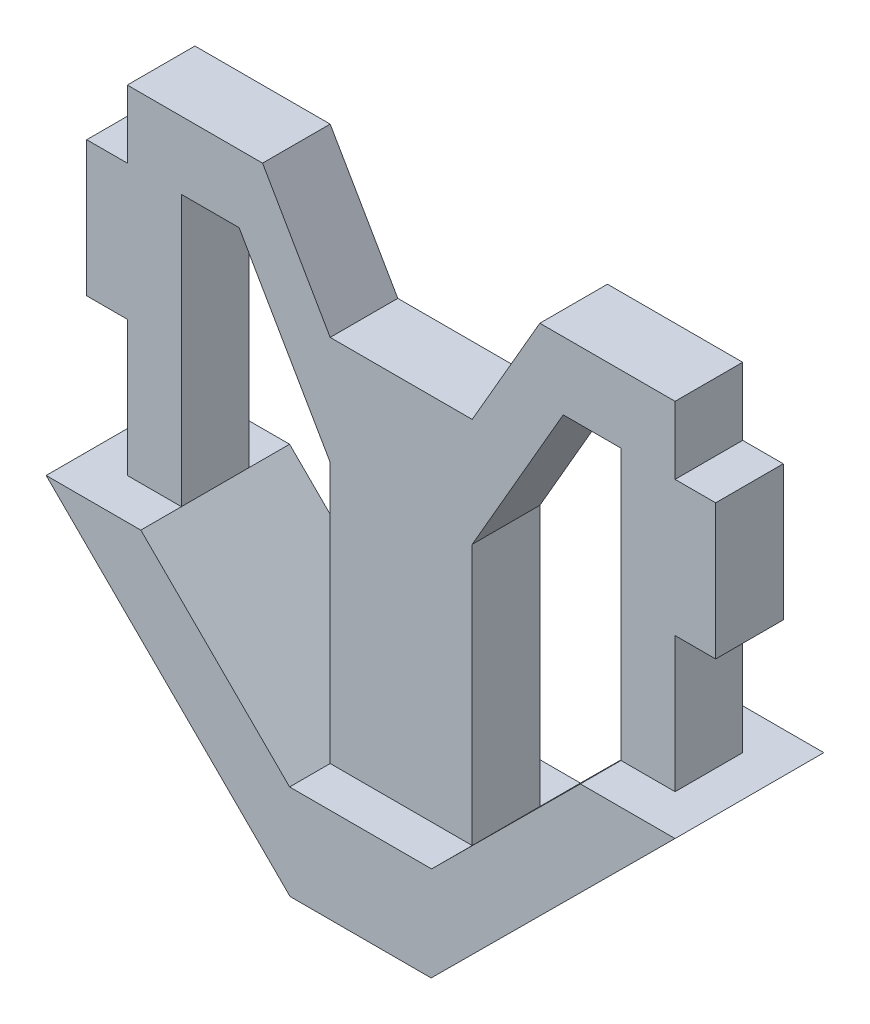
SolidWorks part; units mm, degrees
ref_plane "Front" through (0, 0, 0) normal (0, 0, 1) x (1, 0, 0)
ref_plane "Top" through (0, 0, 0) normal (0, 1, 0) x (1, 0, 0)
ref_plane "Right" through (0, 0, 0) normal (1, 0, 0) x (0, 0, -1)
sketch "草图1" plane through (0, 0, 0) normal (0, 0, 1) x (1, 0, 0)
  line L0 (0, 31.8102) -> (0, 0) construction
  line L1 (-5.2514, 27.286) -> (5.2514, 27.286)
  line L2 (5.2514, 27.286) -> (10.2514, 35.9462)
  line L3 (10.2514, 35.9462) -> (20.2514, 35.9462)
  line L4 (-5.2514, 27.286) -> (-10.2514, 35.9462)
  line L5 (-5.2514, 19.286) -> (-11.9835, 30.9462)
  line L6 (20.2514, 35.9462) -> (20.2514, 30.9462)
  line L7 (20.2514, 30.9462) -> (23.2514, 30.9462)
  line L8 (23.2514, 30.9462) -> (23.2514, 20.9462)
  line L9 (23.2514, 20.9462) -> (20.2514, 20.9462)
  line L10 (20.2514, 20.9462) -> (20.2514, 10.9462)
  line L11 (20.2514, 10.9462) -> (16.2514, 10.9462)
  line L12 (-20.2514, 35.9462) -> (-20.2514, 30.9462)
  line L13 (-20.2514, 30.9462) -> (-23.2514, 30.9462)
  line L14 (-23.2514, 30.9462) -> (-23.2514, 20.9462)
  line L15 (-23.2514, 20.9462) -> (-20.2514, 20.9462)
  line L16 (-20.2514, 20.9462) -> (-20.2514, 10.9462)
  line L17 (-20.2514, 10.9462) -> (-16.2514, 10.9462)
  line L18 (-16.2514, 10.9462) -> (-16.2514, 30.9462)
  line L19 (16.2514, 10.9462) -> (16.2514, 30.9462)
  line L20 (-16.2514, 30.9462) -> (-11.9835, 30.9462)
  line L21 (-8.7155, 25.286) -> (-13.7155, 33.9462) construction
  line L22 (-20.2514, 35.9462) -> (-10.2514, 35.9462)
  line L23 (-5.2514, 19.286) -> (-5.2514, 0)
  line L24 (0, 0) -> (5.2514, 0)
  line L25 (5.2514, 19.286) -> (5.2514, 0)
  line L26 (5.2514, 19.286) -> (11.9835, 30.9462)
  line L27 (16.2514, 30.9462) -> (11.9835, 30.9462)
  line L28 (0, 0) -> (-5.2514, 0)
  point P6 (0, 27.286)
  point P27 (0, 27.286)
  point P32 (0, 10.9462)
  dimension "D1" = 5
  dimension "D2" = 4
extrude "凸台-拉伸1" add sketch "草图1" along normal mid plane 5
sketch "草图2" plane through (0, 0, 0) normal (0, 0, 1) x (1, 0, 0)
  line L0 (16.2514, 10.9462) -> (23.2514, 10.9462)
  line L1 (0, 0) -> (0, 13.7363) construction
  line L2 (5.217, -7) -> (0, -7)
  line L3 (5.2514, 0) -> (0, 0)
  line L4 (23.2514, 10.9462) -> (5.217, -7)
  line L5 (5.2514, 0) -> (16.2514, 10.9462)
  line L6 (-5.217, -7) -> (0, -7)
  line L7 (-23.2514, 10.9462) -> (-5.217, -7)
  line L8 (-16.2514, 10.9462) -> (-23.2514, 10.9462)
  line L9 (-5.2514, 0) -> (-16.2514, 10.9462)
  line L10 (-5.2514, 0) -> (0, 0)
  line L11 (5.2514, -7) -> (0, -7) construction
  dimension "D1" = 7
extrude "凸台-拉伸2" add sketch "草图2" along normal mid plane 11
